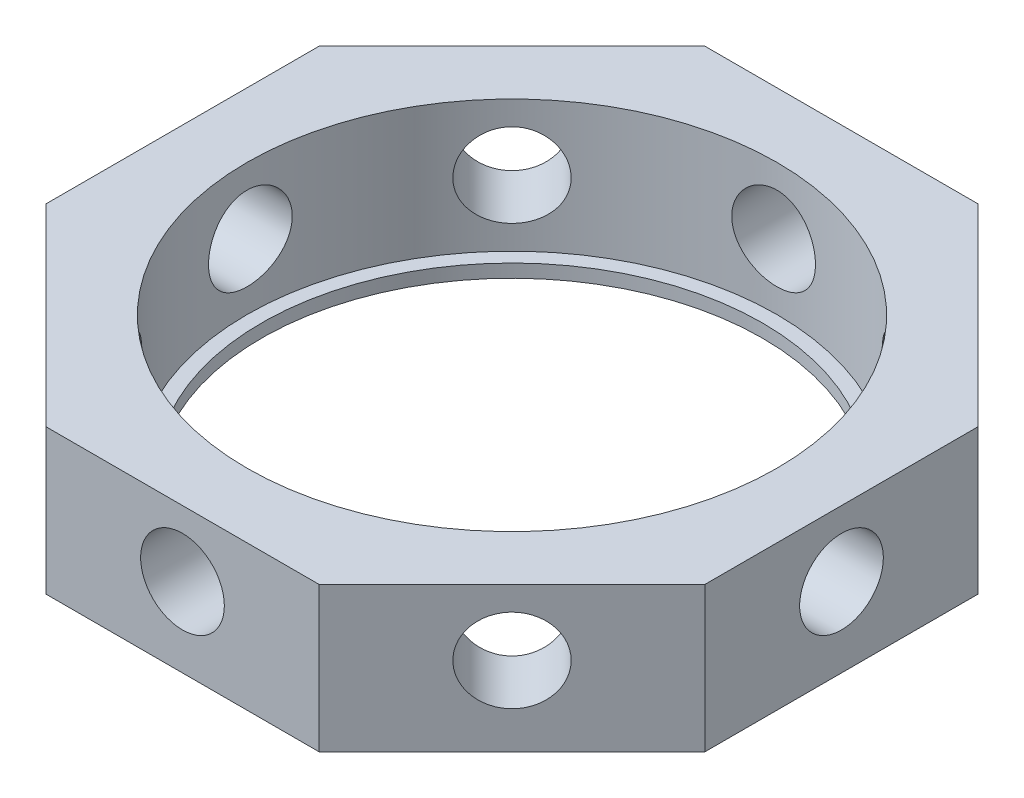
SolidWorks part; units mm, degrees
material "ABS"
ref_plane "Front Plane" through (0, 0, 0) normal (0, 0, 1) x (1, 0, 0)
ref_plane "Top Plane" through (0, 0, 0) normal (0, 1, 0) x (1, 0, 0)
ref_plane "Right Plane" through (0, 0, 0) normal (1, 0, 0) x (0, 0, -1)
sketch "Sketch1" plane through (0, 0, 0) normal (0, 1, 0) x (1, 0, 0)
  line L1 (63.5, 26.3026) -> (26.3026, 63.5)
  line L2 (26.3026, 63.5) -> (-26.3026, 63.5)
  line L3 (-26.3026, 63.5) -> (-63.5, 26.3026)
  line L4 (-63.5, 26.3026) -> (-63.5, -26.3026)
  line L5 (-63.5, -26.3026) -> (-26.3026, -63.5)
  line L6 (-26.3026, -63.5) -> (26.3026, -63.5)
  line L7 (26.3026, -63.5) -> (63.5, -26.3026)
  line L8 (63.5, -26.3026) -> (63.5, 26.3026)
  circle A0 centre (0, 0) radius 51.054
  circle A1 centre (0, 0) radius 63.5 construction
  dimension "D1" = 102.108
  dimension "D2" = 63.5
extrude "Boss-Extrude1" add sketch "Sketch1" along normal blind 25.4
sketch "Sketch2" plane through (63.5, 0, 0) normal (1, 0, 0) x (0, 0, -1)
  circle A0 centre (0, 12.7) radius 8.0645
  point P2 (0, 0)
  dimension "D1" = 16.129
  dimension "D2" = 12.7
extrude "Cut-Extrude1" cut sketch "Sketch2" against normal blind 31.75
pattern_circular "CirPattern1" count 8 over 360 about axis through (0, 25.4, 0) along (0, -1, 0) of "Cut-Extrude1"
sketch "Sketch3" plane through (0, 0, 0) normal (0, -1, 0) x (1, 0, 0)
  line L1 (26.3026, 63.5) -> (-26.3026, 63.5)
  line L2 (-26.3026, 63.5) -> (-63.5, 26.3026)
  line L3 (-63.5, 26.3026) -> (-63.5, -26.3026)
  line L4 (-63.5, -26.3026) -> (-26.3026, -63.5)
  line L5 (-26.3026, -63.5) -> (26.3026, -63.5)
  line L6 (26.3026, -63.5) -> (63.5, -26.3026)
  line L7 (63.5, -26.3026) -> (63.5, 26.3026)
  line L8 (63.5, 26.3026) -> (26.3026, 63.5)
  circle A0 centre (0, 0) radius 48.26
  circle A1 centre (0, 0) radius 63.5 construction
  point P3 (26.3026, 63.5)
  dimension "D1" = 96.52
extrude "Boss-Extrude2" add sketch "Sketch3" along normal blind 2.54
